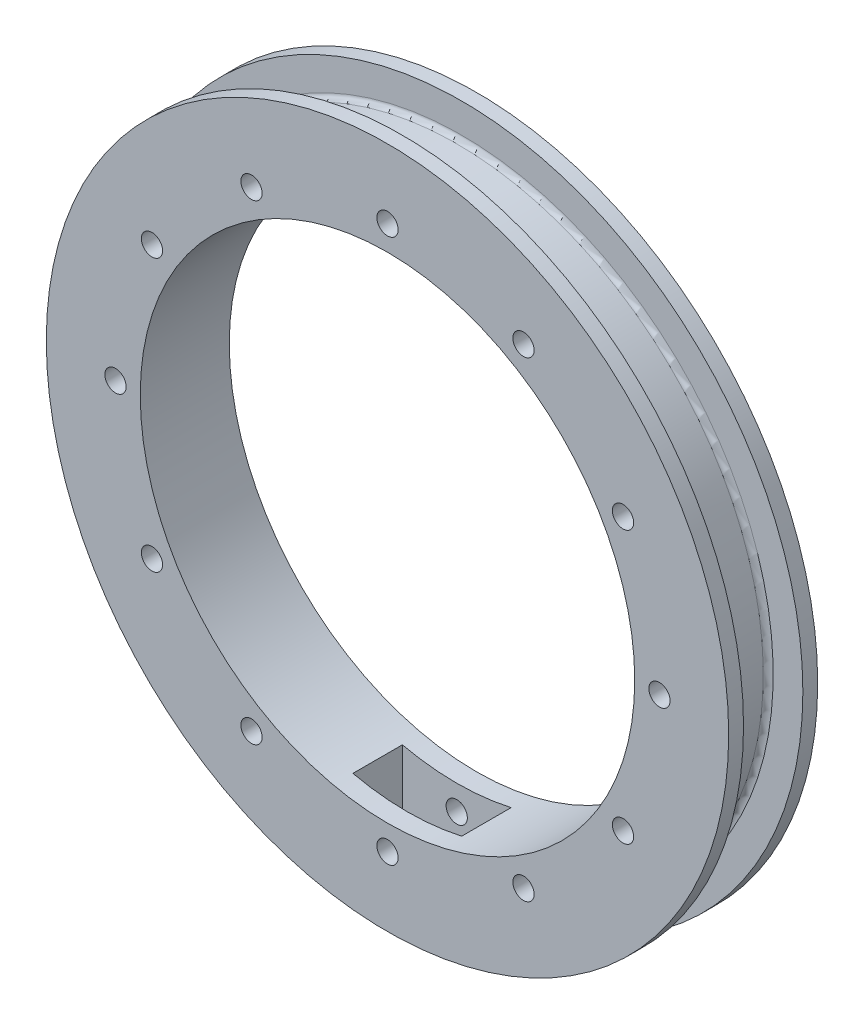
SolidWorks part; units mm, degrees
material "ABS"
ref_plane "前视基准面" through (0, 0, 0) normal (0, 0, 1) x (1, 0, 0)
ref_plane "上视基准面" through (0, 0, 0) normal (0, 1, 0) x (1, 0, 0)
ref_plane "右视基准面" through (0, 0, 0) normal (1, 0, 0) x (0, 0, -1)
other "Configuration Table"
sketch "草图1" plane through (0, 0, 0) normal (0, 0, 1) x (1, 0, 0)
  circle A0 centre (0, 0) radius 62
  dimension "D1" = 124
extrude "凸台-拉伸1" add sketch "草图1" along normal mid plane 12
sketch "草图2" plane through (0, 0, -6) normal (0, 0, -1) x (-1, 0, 0)
  circle A0 centre (0, 0) radius 69
  dimension "D1" = 138
extrude "凸台-拉伸2" add sketch "草图2" along normal blind 3
sketch "草图3" plane through (0, 0, 6) normal (0, 0, 1) x (1, 0, 0)
  circle A0 centre (0, 0) radius 69
  dimension "D1" = 138
extrude "凸台-拉伸3" add sketch "草图3" along normal blind 3
fillet "圆角1" radius 1 2 edges at (62, 0, -6) (62, 0, 6)
sketch "草图4" plane through (0, 0, 0) normal (0, 1, 0) x (1, 0, 0)
  line L0 (-62, 5) -> (62, 5) construction
  line L1 (11, -5) -> (-11, -5)
  line L2 (11, -5) -> (11, 5)
  line L3 (11, 5) -> (-11, 5)
  line L4 (-11, -5) -> (-11, 5)
  line L5 (11, -5) -> (-11, 5) construction
  line L6 (11, 5) -> (-11, -5) construction
  point P0 (0, 0)
  dimension "D1" = 22
extrude "切除-拉伸1" cut sketch "草图4" against normal blind 133
sketch "草图5" plane through (0, 0, -9) normal (0, 0, -1) x (-1, 0, 0)
  circle A0 centre (0, 0) radius 50
  dimension "D1" = 100
extrude "切除-拉伸2" cut sketch "草图5" against normal blind 133
sketch "草图6" plane through (0, 0, -9) normal (0, 0, -1) x (-1, 0, 0)
  circle A0 centre (0, 0) radius 55 construction
  circle A1 centre (0, 55) radius 2.15
  circle A2 centre (27.5, 47.6314) radius 2.15
  circle A3 centre (47.6314, 27.5) radius 2.15
  circle A4 centre (55, 0) radius 2.15
  circle A5 centre (47.6314, -27.5) radius 2.15
  circle A6 centre (27.5, -47.6314) radius 2.15
  circle A7 centre (0, -55) radius 2.15
  circle A8 centre (-27.5, -47.6314) radius 2.15
  circle A9 centre (-47.6314, -27.5) radius 2.15
  circle A10 centre (-55, 0) radius 2.15
  circle A11 centre (-47.6314, 27.5) radius 2.15
  circle A12 centre (-27.5, 47.6314) radius 2.15
  point P29 (0, 0)
  dimension "D1" = 110
  dimension "D2" = 4.3
  dimension "D3" = 12
extrude "切除-拉伸3" cut sketch "草图6" against normal blind 133
